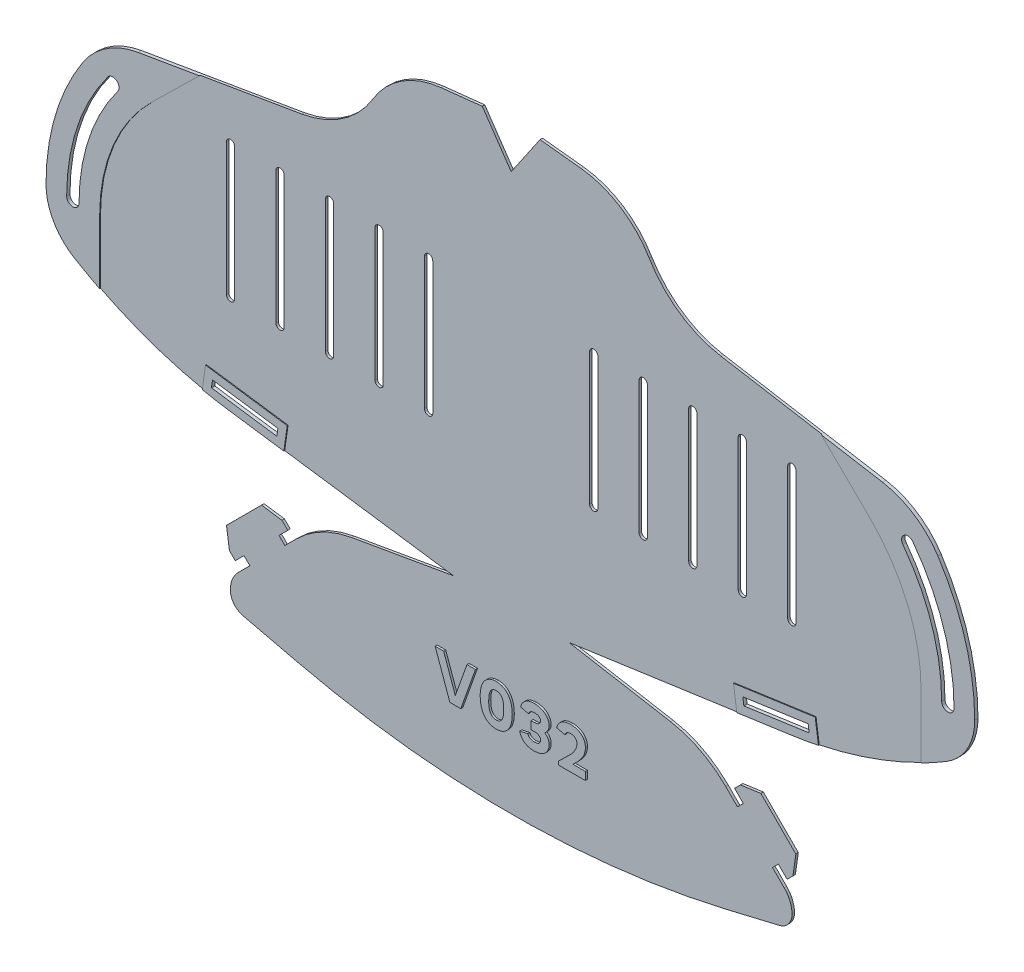
SolidWorks part; units mm, degrees
ref_plane "Front Plane" through (0, 0, 0) normal (0, 0, 1) x (1, 0, 0)
ref_plane "Top Plane" through (0, 0, 0) normal (0, 1, 0) x (1, 0, 0)
ref_plane "Right Plane" through (0, 0, 0) normal (1, 0, 0) x (0, 0, -1)
sketch "Sketch1" plane through (0, 0, 0) normal (0, 0, 1) x (1, 0, 0)
  line L0 (0, 0) -> (0, -145) construction
  line L1 (-14, -102) -> (14, -102) construction
  line L2 (-112.5, -69) -> (112.5, -69) construction
  line L3 (0, -10.2352) -> (-7, 0)
  line L4 (0, -10.2352) -> (7, 0)
  line L5 (7, 0) -> (16.9419, -1.0768)
  line L6 (-90.1804, -30.1909) -> (-50.7439, -23.5)
  line L7 (90.1804, -30.1909) -> (50.7439, -23.5)
  line L8 (-14, -102) -> (-68.2662, -94.2919)
  line L9 (-7, 0) -> (-16.9419, -1.0768)
  line L10 (14, -102) -> (68.2662, -94.2919)
  line L11 (-103.5977, -39) -> (-103.5977, -69) construction
  line L12 (-14, -102) -> (-38.6266, -106.305)
  line L13 (-52, -113.2546) -> (-54.8283, -116.0832)
  line L14 (52, -113.2546) -> (54.8283, -116.0832)
  line L15 (14, -102) -> (38.6266, -106.305)
  line L16 (-54.8283, -116.0832) -> (-56.2426, -114.669)
  line L17 (-56.2426, -114.669) -> (-54.1214, -112.5476)
  line L18 (-54.1214, -112.5476) -> (-55.5356, -111.1334)
  line L19 (-55.5356, -111.1334) -> (-60.4854, -110.4265)
  line L20 (-60.4854, -110.4265) -> (-68.9703, -118.9122)
  line L21 (-64.7275, -123.1546) -> (-63.3132, -124.5688)
  line L22 (-63.3132, -124.5688) -> (-66.1415, -127.3973)
  line L23 (-64.7275, -123.1546) -> (-66.8487, -125.2761)
  line L24 (-66.8487, -125.2761) -> (-68.263, -123.8619)
  line L25 (-68.9703, -118.9122) -> (-68.263, -123.8619)
  line L26 (68.9703, -118.9122) -> (68.263, -123.8619)
  line L27 (66.8487, -125.2761) -> (68.263, -123.8619)
  line L28 (64.7275, -123.1546) -> (66.8487, -125.2761)
  line L29 (63.3132, -124.5688) -> (66.1415, -127.3973)
  line L30 (64.7275, -123.1546) -> (63.3132, -124.5688)
  line L31 (60.4854, -110.4265) -> (68.9703, -118.9122)
  line L32 (55.5356, -111.1334) -> (60.4854, -110.4265)
  line L33 (54.1214, -112.5476) -> (55.5356, -111.1334)
  line L34 (56.2426, -114.669) -> (54.1214, -112.5476)
  line L35 (54.8283, -116.0832) -> (56.2426, -114.669)
  line L36 (-64.9691, -135.8852) -> (-52.4361, -138.8607)
  line L37 (64.9691, -135.8852) -> (52.4361, -138.8607)
  line L38 (-68.9703, -118.9122) -> (-64.7275, -123.1546) construction
  line L39 (-60.4854, -110.4265) -> (-56.2426, -114.669) construction
  arc A0 (-16.9419, -1.0768) -> (-33.4614, -11.6696) centre (-14.5729, -22.9489) ccw
  arc A1 (-33.4614, -11.6696) -> (-50.7439, -23.5) centre (-54.9257, 1.1478) cw
  arc A2 (-103.5977, -39) -> (-90.1804, -30.1909) centre (-86.8349, -49.9091) cw
  arc A3 (-112.5, -69) -> (-103.5977, -39) centre (-57.5, -69) cw
  arc A4 (112.5, -69) -> (103.5977, -39) centre (57.5, -69) ccw
  arc A5 (103.5977, -39) -> (90.1804, -30.1909) centre (86.8349, -49.9091) ccw
  arc A6 (16.9419, -1.0768) -> (33.4614, -11.6696) centre (14.5729, -22.9489) cw
  arc A7 (33.4614, -11.6696) -> (50.7439, -23.5) centre (54.9257, 1.1478) ccw
  arc A8 (-112.5, -69) -> (-105.7111, -81) centre (-98.5, -69) ccw
  arc A9 (-105.7111, -81) -> (-68.2662, -94.2919) centre (-54.2032, 4.7143) ccw
  arc A10 (112.5, -69) -> (105.7111, -81) centre (98.5, -69) cw
  arc A11 (105.7111, -81) -> (68.2662, -94.2919) centre (54.2032, 4.7143) cw
  arc A12 (-38.6266, -106.305) -> (-52, -113.2546) centre (-34.3216, -130.9315) ccw
  arc A13 (38.6266, -106.305) -> (52, -113.2546) centre (34.3216, -130.9315) cw
  arc A14 (-66.1415, -127.3973) -> (-68.0451, -131.9933) centre (-61.5451, -131.9933) ccw
  arc A15 (-68.0451, -131.9933) -> (-64.9691, -135.8852) centre (-64.0451, -131.9933) ccw
  arc A16 (68.0451, -131.9933) -> (64.9691, -135.8852) centre (64.0451, -131.9933) cw
  arc A17 (66.1415, -127.3973) -> (68.0451, -131.9933) centre (61.5451, -131.9933) cw
  arc A19 (-52.4361, -138.8607) -> (0, -145) centre (0, 82) ccw
  arc A20 (52.4361, -138.8607) -> (0, -145) centre (0, 82) cw
  point P8 (0, -102)
  point P11 (0, -69)
  dimension "D5" = 55
  dimension "D11" = 20
  dimension "D13" = 25
  dimension "D16" = 14
  dimension "D15" = 22
  dimension "D18" = 100
  dimension "D22" = 25
  dimension "D31" = 6.5
  dimension "D32" = 4
  dimension "D34" = 227
  dimension "D1" = 145
  dimension "D2" = 28
  dimension "D3" = 43
  dimension "D4" = 76
  dimension "D6" = 225
  dimension "D7" = 14
  dimension "D8" = 12.4
  dimension "D9" = 10
  dimension "D10" = 30
  dimension "D12" = 40
  dimension "D14" = 45.5
  dimension "D17" = 12
  dimension "D19" = 18
  dimension "D20" = 25
  dimension "D21" = 4
  dimension "D23" = 38
  dimension "D24" = 2
  dimension "D25" = 3
  dimension "D26" = 2
  dimension "D27" = 18
  dimension "D29" = 8
  dimension "D30" = 4
extrude "Main Shape" add sketch "Sketch1" along normal blind 0.6
sketch "Sketch2" plane through (0, 0, 0.6) normal (0, 0, 1) x (1, 0, 0)
  line L0 (0, -55) -> (0, 55) construction
  arc A0 (-96.3, -39.9) -> (-106, -69) centre (-57.5, -69) ccw construction
  arc A1 (-97.5, -39) -> (-107.5, -69) centre (-57.5, -69) ccw
  arc A2 (-95.1, -40.8) -> (-104.5, -69) centre (-57.5, -69) ccw
  arc A3 (-95.1, -40.8) -> (-97.5, -39) centre (-96.3, -39.9) ccw
  arc A4 (-107.5, -69) -> (-104.5, -69) centre (-106, -69) ccw
  arc A6 (-103.5977, -39) -> (-112.5, -69) centre (-57.5, -69) ccw construction
  arc A7 (96.3, -39.9) -> (106, -69) centre (57.5, -69) cw construction
  arc A8 (97.5, -39) -> (107.5, -69) centre (57.5, -69) cw
  arc A9 (95.1, -40.8) -> (104.5, -69) centre (57.5, -69) cw
  arc A10 (95.1, -40.8) -> (97.5, -39) centre (96.3, -39.9) cw
  arc A11 (107.5, -69) -> (104.5, -69) centre (106, -69) cw
  point P3 (-103.5111, -53.663)
  point P19 (103.5111, -53.663)
  dimension "D1" = 5
  dimension "D2" = 1.5
extrude "Elastic Attachment Points" cut sketch "Sketch2" against normal through all
sketch "Sketch7" plane through (0, 0, 0.6) normal (0, 0, 1) x (1, 0, 0)
  line L0 (-99.5, -69) -> (-99.5, -84.4384)
  line L1 (-86.8939, -39) -> (-75.3319, -27.6717)
  line L2 (-50.7439, -23.5) -> (-90.1804, -30.1909) construction
  line L3 (-75.3319, -27.6717) -> (-90.1804, -30.1909)
  line L4 (0, -55) -> (0, 55) construction
  line L5 (75.3319, -27.6717) -> (90.1804, -30.1909)
  line L6 (86.8939, -39) -> (75.3319, -27.6717)
  line L7 (99.5, -69) -> (99.5, -84.4384)
  arc A0 (-99.5, -69) -> (-86.8939, -39) centre (-57.5, -69) cw
  arc A1 (-95.1, -40.8) -> (-104.5, -69) centre (-57.5, -69) ccw construction
  arc A2 (-105.7111, -81) -> (-68.2662, -94.2919) centre (-54.2032, 4.7143) ccw construction
  arc A3 (-112.5, -69) -> (-105.7111, -81) centre (-98.5, -69) ccw construction
  arc A4 (-103.5977, -39) -> (-112.5, -69) centre (-57.5, -69) ccw construction
  arc A5 (-90.1804, -30.1909) -> (-103.5977, -39) centre (-86.8349, -49.9091) ccw construction
  arc A6 (-105.7111, -81) -> (-99.5, -84.4384) centre (-54.2032, 4.7143) ccw
  arc A7 (-112.5, -69) -> (-105.7111, -81) centre (-98.5, -69) ccw
  arc A8 (-103.5977, -39) -> (-112.5, -69) centre (-57.5, -69) ccw
  arc A9 (-90.1804, -30.1909) -> (-103.5977, -39) centre (-86.8349, -49.9091) ccw
  arc A10 (90.1804, -30.1909) -> (103.5977, -39) centre (86.8349, -49.9091) cw
  arc A11 (103.5977, -39) -> (112.5, -69) centre (57.5, -69) cw
  arc A12 (112.5, -69) -> (105.7111, -81) centre (98.5, -69) cw
  arc A13 (105.7111, -81) -> (99.5, -84.4384) centre (54.2032, 4.7143) cw
  arc A14 (99.5, -69) -> (86.8939, -39) centre (57.5, -69) ccw
  arc A15 (-107.5, -69) -> (-104.5, -69) centre (-106, -69) ccw construction
  arc A16 (-95.1, -40.8) -> (-97.5, -39) centre (-96.3, -39.9) ccw construction
  arc A17 (-97.5, -39) -> (-107.5, -69) centre (-57.5, -69) ccw construction
  arc A18 (-107.5, -69) -> (-104.5, -69) centre (-106, -69) ccw
  arc A19 (-95.1, -40.8) -> (-97.5, -39) centre (-96.3, -39.9) ccw
  arc A20 (-95.1, -40.8) -> (-104.5, -69) centre (-57.5, -69) ccw
  arc A21 (-97.5, -39) -> (-107.5, -69) centre (-57.5, -69) ccw
  arc A22 (104.5, -69) -> (107.5, -69) centre (106, -69) ccw construction
  arc A23 (97.5, -39) -> (95.1, -40.8) centre (96.3, -39.9) ccw construction
  arc A24 (104.5, -69) -> (95.1, -40.8) centre (57.5, -69) ccw construction
  arc A25 (107.5, -69) -> (97.5, -39) centre (57.5, -69) ccw construction
  arc A26 (104.5, -69) -> (107.5, -69) centre (106, -69) ccw
  arc A27 (97.5, -39) -> (95.1, -40.8) centre (96.3, -39.9) ccw
  arc A28 (104.5, -69) -> (95.1, -40.8) centre (57.5, -69) ccw
  arc A29 (107.5, -69) -> (97.5, -39) centre (57.5, -69) ccw
  dimension "D1" = 5
extrude "Reinforced Attachment Points" add sketch "Sketch7" along normal blind 0.2
sketch "Sketch6" plane through (0, 0, 0.6) normal (0, 0, 1) x (1, 0, 0)
  line L0 (-72.4096, -91.6833) -> (-56.5686, -93.9334)
  line L1 (-56.5686, -93.9334) -> (-56.3155, -92.1513)
  line L2 (-56.3155, -92.1513) -> (-72.1565, -89.9012)
  line L3 (-72.1565, -89.9012) -> (-72.4096, -91.6833)
  line L4 (-68.2662, -94.2919) -> (-14, -102) construction
  line L5 (-64.236, -91.0263) -> (-64.4891, -92.8084) construction
  line L13 (0, -0.44) -> (0, 0.44) construction
  line L14 (64.236, -91.0263) -> (64.4891, -92.8084) construction
  line L15 (72.4096, -91.6833) -> (72.1565, -89.9012)
  line L16 (56.3155, -92.1513) -> (56.5686, -93.9334)
  line L22 (56.3155, -92.1513) -> (72.1565, -89.9012)
  line L24 (72.4096, -91.6833) -> (56.5686, -93.9334)
  dimension "D1" = 2
  dimension "D2" = 16
  dimension "D3" = 51.28
  dimension "D4" = 1.8
extrude "Tab Slits" cut sketch "Sketch6" against normal through all
sketch "Sketch9" plane through (0, 0, 0.6) normal (0, 0, 1) x (1, 0, 0)
  line L4 (-56.5686, -93.9334) -> (-56.3155, -92.1513) construction
  line L5 (-72.4096, -91.6833) -> (-56.5686, -93.9334) construction
  line L6 (-72.1565, -89.9012) -> (-72.4096, -91.6833) construction
  line L7 (-56.3155, -92.1513) -> (-72.1565, -89.9012) construction
  line L12 (-56.5686, -93.9334) -> (-56.3155, -92.1513)
  line L13 (-72.4096, -91.6833) -> (-56.5686, -93.9334)
  line L14 (-72.1565, -89.9012) -> (-72.4096, -91.6833)
  line L15 (-56.3155, -92.1513) -> (-72.1565, -89.9012)
  line L16 (-54.8698, -96.1948) -> (-54.0541, -90.4524)
  line L17 (-68.2662, -94.2919) -> (-14, -102) construction
  line L18 (-54.0541, -90.4524) -> (-73.8554, -87.6398)
  line L19 (-73.8554, -87.6398) -> (-74.6416, -93.1748)
  line L20 (-68.2662, -94.2919) -> (-54.8698, -96.1948)
  line L21 (0, -0.44) -> (0, 0.44) construction
  line L22 (68.2662, -94.2919) -> (54.8698, -96.1948)
  line L23 (73.8554, -87.6398) -> (74.6416, -93.1748)
  line L24 (54.0541, -90.4524) -> (73.8554, -87.6398)
  line L25 (54.8698, -96.1948) -> (54.0541, -90.4524)
  line L26 (56.3155, -92.1513) -> (72.1565, -89.9012)
  line L27 (72.1565, -89.9012) -> (72.4096, -91.6833)
  line L28 (72.4096, -91.6833) -> (56.5686, -93.9334)
  line L29 (56.5686, -93.9334) -> (56.3155, -92.1513)
  arc A0 (-99.5, -84.4384) -> (-68.2662, -94.2919) centre (-54.2032, 4.7143) ccw construction
  arc A1 (-74.6416, -93.1748) -> (-68.2662, -94.2919) centre (-54.2032, 4.7143) ccw
  arc A2 (74.6416, -93.1748) -> (68.2662, -94.2919) centre (54.2032, 4.7143) cw
  dimension "D1" = 2
  dimension "D2" = 2
  dimension "D3" = 2
extrude "Reinforced Tab Slits" add sketch "Sketch9" along normal blind 0.2
sketch "Sketch3" plane through (0, 0, 0.6) normal (0, 0, 1) x (1, 0, 0)
  line L0 (-20, -38.45) -> (-20, -70.45) construction
  line L1 (-19, -38.45) -> (-19, -70.45)
  line L2 (-21, -38.45) -> (-21, -70.45)
  line L3 (0, -10.2352) -> (0, -145) construction
  line L4 (-106, -69) -> (-96.3, -69) construction
  line L5 (-96.3, -69) -> (-96.3, -39.9) construction
  line L6 (-32, -38.45) -> (-32, -70.45) construction
  line L7 (-31, -38.45) -> (-31, -70.45)
  line L8 (-33, -38.45) -> (-33, -70.45)
  line L9 (-44, -38.45) -> (-44, -70.45) construction
  line L10 (-43, -38.45) -> (-43, -70.45)
  line L11 (-45, -38.45) -> (-45, -70.45)
  line L12 (-56, -38.45) -> (-56, -70.45) construction
  line L13 (-55, -38.45) -> (-55, -70.45)
  line L14 (-57, -38.45) -> (-57, -70.45)
  line L15 (-68, -38.45) -> (-68, -70.45) construction
  line L16 (-67, -38.45) -> (-67, -70.45)
  line L17 (-69, -38.45) -> (-69, -70.45)
  line L18 (20, -38.45) -> (20, -70.45) construction
  line L19 (19, -38.45) -> (19, -70.45)
  line L20 (21, -38.45) -> (21, -70.45)
  line L21 (32, -38.45) -> (32, -70.45) construction
  line L22 (31, -38.45) -> (31, -70.45)
  line L23 (33, -38.45) -> (33, -70.45)
  line L24 (44, -38.45) -> (44, -70.45) construction
  line L25 (43, -38.45) -> (43, -70.45)
  line L26 (45, -38.45) -> (45, -70.45)
  line L27 (56, -38.45) -> (56, -70.45) construction
  line L28 (55, -38.45) -> (55, -70.45)
  line L29 (57, -38.45) -> (57, -70.45)
  line L30 (68, -38.45) -> (68, -70.45) construction
  line L31 (67, -38.45) -> (67, -70.45)
  line L32 (69, -38.45) -> (69, -70.45)
  arc A0 (-19, -38.45) -> (-21, -38.45) centre (-20, -38.45) ccw
  arc A1 (-21, -70.45) -> (-19, -70.45) centre (-20, -70.45) ccw
  arc A2 (-52.4361, -138.8607) -> (52.4361, -138.8607) centre (0, 82) ccw construction
  arc A3 (-31, -38.45) -> (-33, -38.45) centre (-32, -38.45) ccw
  arc A4 (-33, -70.45) -> (-31, -70.45) centre (-32, -70.45) ccw
  arc A5 (-43, -38.45) -> (-45, -38.45) centre (-44, -38.45) ccw
  arc A6 (-45, -70.45) -> (-43, -70.45) centre (-44, -70.45) ccw
  arc A7 (-55, -38.45) -> (-57, -38.45) centre (-56, -38.45) ccw
  arc A8 (-57, -70.45) -> (-55, -70.45) centre (-56, -70.45) ccw
  arc A9 (-67, -38.45) -> (-69, -38.45) centre (-68, -38.45) ccw
  arc A10 (-69, -70.45) -> (-67, -70.45) centre (-68, -70.45) ccw
  arc A11 (19, -38.45) -> (21, -38.45) centre (20, -38.45) cw
  arc A12 (21, -70.45) -> (19, -70.45) centre (20, -70.45) cw
  arc A13 (31, -38.45) -> (33, -38.45) centre (32, -38.45) cw
  arc A14 (33, -70.45) -> (31, -70.45) centre (32, -70.45) cw
  arc A15 (43, -38.45) -> (45, -38.45) centre (44, -38.45) cw
  arc A16 (45, -70.45) -> (43, -70.45) centre (44, -70.45) cw
  arc A17 (55, -38.45) -> (57, -38.45) centre (56, -38.45) cw
  arc A18 (57, -70.45) -> (55, -70.45) centre (56, -70.45) cw
  arc A19 (67, -38.45) -> (69, -38.45) centre (68, -38.45) cw
  arc A20 (69, -70.45) -> (67, -70.45) centre (68, -70.45) cw
  point P2 (-20, -54.45)
  point P13 (-19, -54.45)
  point P16 (-96.3, -54.45)
  point P20 (-32, -54.45)
  point P31 (-44, -54.45)
  point P38 (-56, -54.45)
  point P45 (-68, -54.45)
  point P52 (20, -54.45)
  point P59 (32, -54.45)
  point P66 (44, -54.45)
  point P73 (56, -54.45)
  point P80 (68, -54.45)
  dimension "D1" = 2
  dimension "D2" = 32
  dimension "D3" = 20
  dimension "D4" = 5
  dimension "D5" = 10
extrude "Breathing Slits" cut sketch "Sketch3" against normal through all
sketch "Sketch8" plane through (0, 0, 0.6) normal (0, 0, 1) x (1, 0, 0)
  line L0 (-67.0266, -128.5) -> (67.0266, -128.5) construction
  line L1 (0, -10.2352) -> (0, -145) construction
  arc A0 (-52.4361, -138.8607) -> (52.4361, -138.8607) centre (0, 82) ccw construction
  arc A1 (-66.1415, -127.3973) -> (-68.0451, -131.9933) centre (-61.5451, -131.9933) ccw construction
  text T0 "<b>V032</b>" font "Double Porter 3" height 10
  point P9 (0, -128.5)
  dimension "D2" = 16.5
extrude "Version Number" add sketch "Sketch8" along normal blind 0.5
